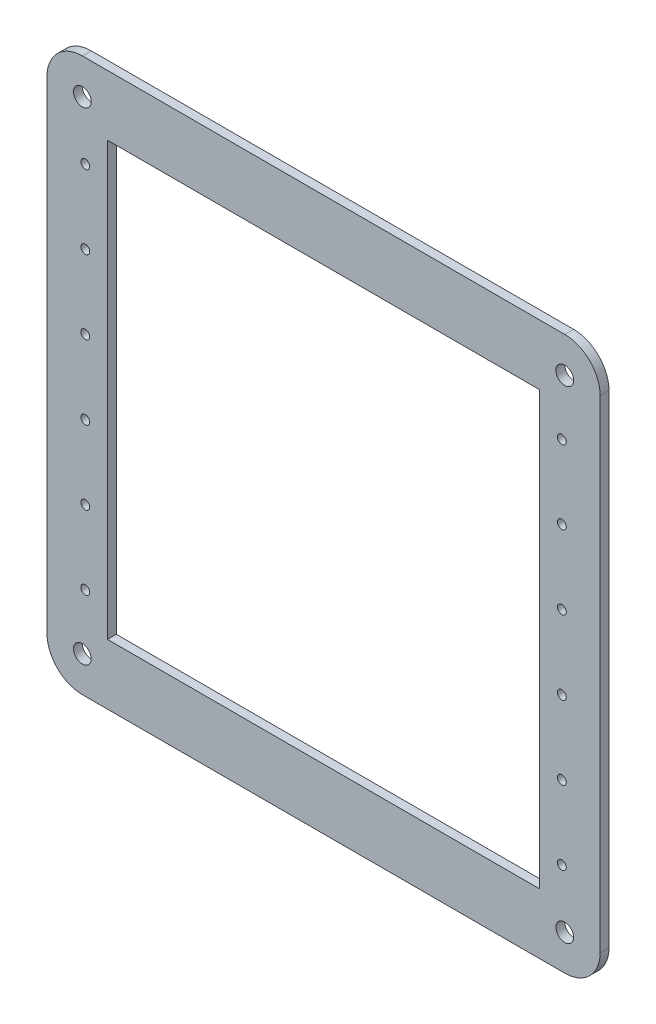
SolidWorks part; units mm, degrees
material "Plain Carbon Steel"
ref_plane "Front Plane" through (0, 0, 0) normal (0, 0, 1) x (1, 0, 0)
ref_plane "Top Plane" through (0, 0, 0) normal (0, 1, 0) x (1, 0, 0)
ref_plane "Right Plane" through (0, 0, 0) normal (1, 0, 0) x (0, 0, -1)
sketch "Sketch1" plane through (0, 0, 0) normal (0, 0, 1) x (1, 0, 0)
  line L0 (-97.6863, 97.6863) -> (97.6863, 97.6863)
  line L1 (-109, 125) -> (109, 125)
  line L2 (-125, 109) -> (-125, -109)
  line L3 (-109, -125) -> (109, -125)
  line L4 (125, 109) -> (125, -109)
  line L5 (-125, 125) -> (125, -125) construction
  line L6 (-125, -125) -> (125, 125) construction
  line L7 (97.6863, 97.6863) -> (97.6863, -97.6863)
  line L8 (97.6863, -97.6863) -> (-97.6863, -97.6863)
  line L9 (-97.6863, -97.6863) -> (-97.6863, 97.6863)
  arc A0 (-125, -109) -> (-109, -125) centre (-109, -109) ccw
  arc A1 (109, -125) -> (125, -109) centre (109, -109) ccw
  arc A2 (109, 125) -> (125, 109) centre (109, 109) cw
  arc A3 (-109, 125) -> (-125, 109) centre (-109, 109) ccw
  circle A4 centre (-109, 109) radius 16 construction
  circle A5 centre (-109, 109) radius 4
  circle A6 centre (109, 109) radius 4
  circle A7 centre (109, -109) radius 4
  circle A8 centre (-109, -109) radius 4
  point P0 (0, 0)
  point P19 (-97.6863, 97.6863)
  dimension "D3" = 16
  dimension "D4" = 8
  dimension "D5" = 8
  dimension "D6" = 8
  dimension "D7" = 8
  dimension "D1" = 250
  dimension "D2" = 250
extrude "Boss-Extrude1" add sketch "Sketch1" along normal blind 4
sketch "Sketch2" plane through (0, 0, 4) normal (0, 0, 1) x (1, 0, 0)
  circle A0 centre (-107.6863, 83.3) radius 2
  circle A1 centre (-107.6863, 50) radius 2
  circle A2 centre (-107.6863, 16.7) radius 2
  circle A3 centre (-107.6863, -16.7) radius 2
  circle A4 centre (-107.6863, -50) radius 2
  circle A5 centre (-107.6863, -83.3) radius 2
  circle A6 centre (107.6863, -83.3) radius 2
  circle A7 centre (107.6863, -50) radius 2
  circle A8 centre (107.6863, -16.7) radius 2
  circle A9 centre (107.6863, 16.7) radius 2
  circle A10 centre (107.6863, 50) radius 2
  circle A11 centre (107.6863, 83.3) radius 2
extrude "Cut-Extrude1" cut sketch "Sketch2" against normal blind 10
ref_point "Point1"
ref_point "Point2"
